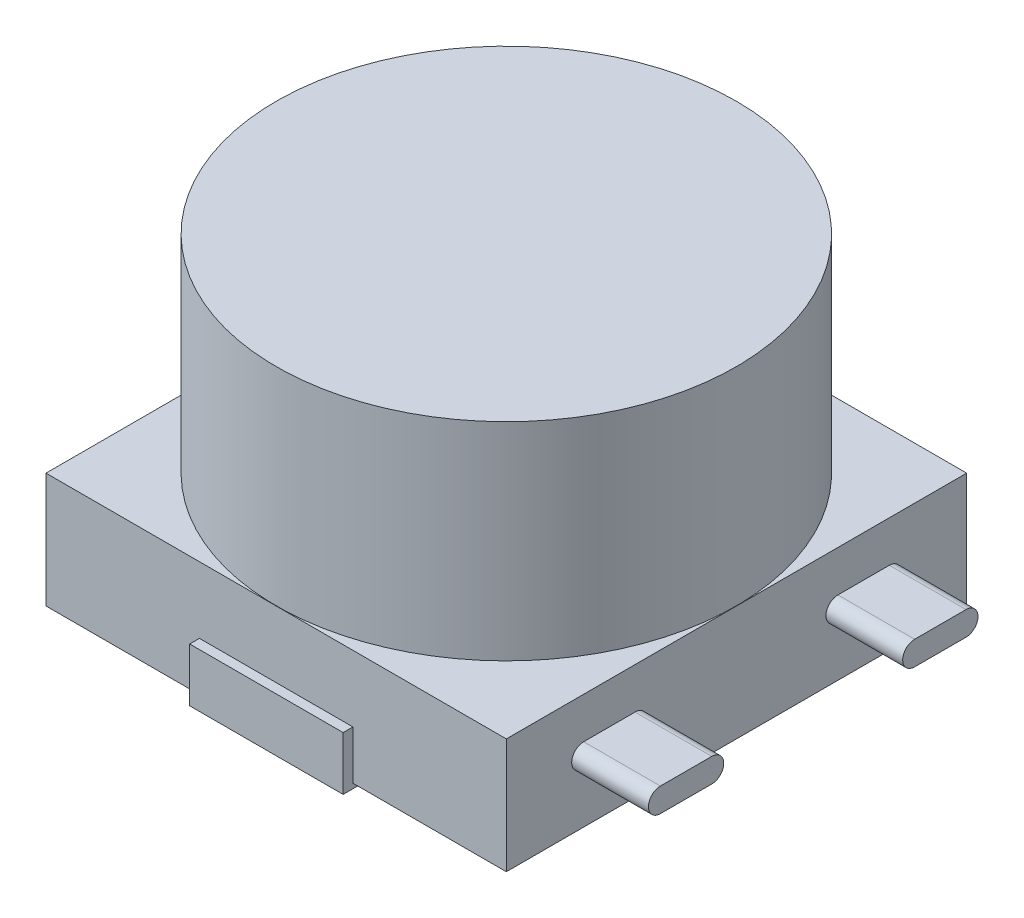
SolidWorks part; units mm, degrees
ref_plane "Front Plane" through (0, 0, 0) normal (0, 0, 1) x (1, 0, 0)
ref_plane "Top Plane" through (0, 0, 0) normal (0, 1, 0) x (1, 0, 0)
ref_plane "Right Plane" through (0, 0, 0) normal (1, 0, 0) x (0, 0, -1)
sketch "Sketch1" plane through (0, 0, 0) normal (0, 1, 0) x (1, 0, 0)
  line L1 (-6, 6) -> (6, 6)
  line L2 (-6, 6) -> (-6, -6)
  line L3 (-6, -6) -> (6, -6)
  line L4 (6, 6) -> (6, -6)
  line L5 (-6, 6) -> (6, -6) construction
  line L6 (-6, -6) -> (6, 6) construction
  point P0 (0, 0)
  dimension "D1" = 12
extrude "Boss-Extrude1" add sketch "Sketch1" along normal blind 3
sketch "Sketch2" plane through (0, 3, 0) normal (0, 1, 0) x (1, 0, 0)
  circle A0 centre (0, 0) radius 5.9953
extrude "Boss-Extrude2" add sketch "Sketch2" along normal blind 5.4
sketch "Sketch3" plane through (6, 0, 0) normal (1, 0, 0) x (0, 0, -1)
  line L0 (-3.9837, 1.6156) -> (-2.6445, 1.6156) construction
  line L1 (-3.9837, 1.9277) -> (-2.6445, 1.9277)
  line L2 (-3.9837, 1.3036) -> (-2.6445, 1.3036)
  line L3 (0, 0) -> (0, 1.5376) construction
  line L4 (3.9837, 1.6156) -> (2.6445, 1.6156) construction
  line L5 (3.9837, 1.9277) -> (2.6445, 1.9277)
  line L6 (3.9837, 1.3036) -> (2.6445, 1.3036)
  arc A0 (-3.9837, 1.9277) -> (-3.9837, 1.3036) centre (-3.9837, 1.6156) ccw
  arc A1 (-2.6445, 1.3036) -> (-2.6445, 1.9277) centre (-2.6445, 1.6156) ccw
  arc A2 (3.9837, 1.9277) -> (3.9837, 1.3036) centre (3.9837, 1.6156) cw
  arc A3 (2.6445, 1.3036) -> (2.6445, 1.9277) centre (2.6445, 1.6156) cw
  point P2 (-3.3141, 1.6156)
  point P12 (3.3141, 1.6156)
extrude "Boss-Extrude3" add sketch "Sketch3" along normal blind 2
sketch "Sketch4" plane through (0, 0, 0) normal (0, -1, 0) x (1, 0, 0)
  line L0 (-6, 6) -> (6, 6) construction
  line L1 (-2, 6.254) -> (2, 6.254)
  line L2 (-2, 6.254) -> (-2, 3.254)
  line L3 (-2, 3.254) -> (2, 3.254)
  line L4 (2, 6.254) -> (2, 3.254)
  line L5 (0, 0) -> (1.3973, 0) construction
  line L6 (2, -6.254) -> (2, -3.254)
  line L7 (-2, -3.254) -> (2, -3.254)
  line L8 (-2, -6.254) -> (-2, -3.254)
  line L9 (-2, -6.254) -> (2, -6.254)
  point P4 (0, 3.254)
  dimension "D1" = 4
  dimension "D2" = 3
  dimension "D3" = 0.254
extrude "Boss-Extrude4" add sketch "Sketch4" along normal blind 0.127 and the other way blind 1.27
